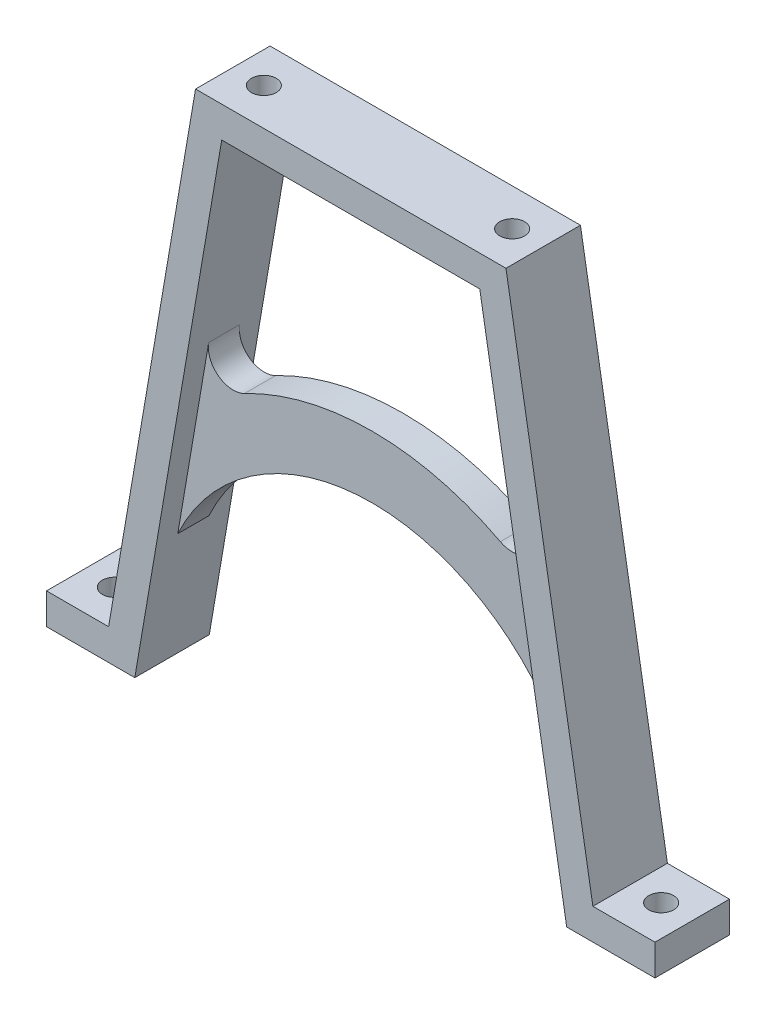
SolidWorks part; units mm, degrees
ref_plane "Front Plane" through (0, 0, 0) normal (0, 0, 1) x (1, 0, 0)
ref_plane "Top Plane" through (0, 0, 0) normal (0, 1, 0) x (1, 0, 0)
ref_plane "Right Plane" through (0, 0, 0) normal (1, 0, 0) x (0, 0, -1)
sketch "Sketch1" plane through (0, 0, 0) normal (0, 0, 1) x (1, 0, 0)
  line L0 (0, 0) -> (0, 95.5483) construction
  line L1 (-49, 0) -> (-34.7813, 0)
  line L2 (-34.7813, 0) -> (-20.7813, 82)
  line L3 (-20.7813, 82) -> (20.7813, 82)
  line L4 (20.7813, 82) -> (34.7813, 0)
  line L5 (34.7813, 0) -> (49, 0)
  line L6 (49, 0) -> (49, 5)
  line L7 (49, 5) -> (39, 5)
  line L8 (39, 5) -> (25, 87)
  line L9 (25, 87) -> (-25, 87)
  line L10 (-25, 87) -> (-39, 5)
  line L11 (-39, 5) -> (-49, 5)
  line L12 (-49, 5) -> (-49, 0)
  point P5 (22.8522, 77.6315)
  point P16 (0, 0)
  dimension "D1" = 87
  dimension "D2" = 5
  dimension "D3" = 5
  dimension "D4" = 5
  dimension "D5" = 5
  dimension "D6" = 25
  dimension "D7" = 49
  dimension "D8" = 10
extrude "Boss-Extrude1" add sketch "Sketch1" along normal mid plane 12
sketch "Sketch2" plane through (0, 0, 0) normal (0, 0, 1) x (1, 0, 0)
  line L0 (0, 0) -> (0, 50) construction
  line L1 (-34.7813, 0) -> (-20.7813, 82) construction
  line L2 (20.7813, 82) -> (34.7813, 0) construction
  line L3 (20.7813, 82) -> (31.4502, 19.5105)
  line L4 (-31.3579, 20.0517) -> (-27.9149, 40.2174)
  arc A0 (-31.3579, 20.0517) -> (31.4502, 19.5105) centre (-0.0768, 5.5001) cw
  arc A1 (-27.9149, 40.2174) -> (27.9395, 40.0737) centre (-0.0768, 5.5001) cw
  arc A2 (-40.4248, 24.2695) -> (40.5885, 23.5715) centre (-0.0768, 5.5001) cw construction
  point P3 (0, 40)
  dimension "D3" = 34.5
  dimension "D1" = 50
  dimension "D2" = 10
  dimension "D4" = 10
extrude "Boss-Extrude2" add sketch "Sketch2" along normal mid plane 5 contours A1 L4 A0 L3
fillet "Fillet1" radius 4 2 edges at (27.9395, 40.0737, 0) (-27.9149, 40.2174, 0)
sketch "Sketch3" plane through (0, 5, 0) normal (0, 1, 0) x (1, 0, 0)
  line L1 (49, -6) -> (49, 6) construction
  circle A0 centre (-44, 0) radius 2
  circle A1 centre (44, 0) radius 2
  point P4 (0, 0)
  point P6 (0, 0)
  point P8 (0, 0)
  dimension "D1" = 4
  dimension "D2" = 5
  dimension "D3" = 5
extrude "Cut-Extrude1" cut sketch "Sketch3" against normal through all
sketch "Sketch4" plane through (0, 87, 0) normal (0, 1, 0) x (1, 0, 0)
  circle A0 centre (-20, 0) radius 2
  circle A1 centre (20, 0) radius 2
  point P4 (0, 0)
  dimension "D1" = 4
  dimension "D2" = 20
  dimension "D3" = 20
extrude "Cut-Extrude2" cut sketch "Sketch4" against normal up to surface (5 mm away) up to face at (0, 82, 0)
